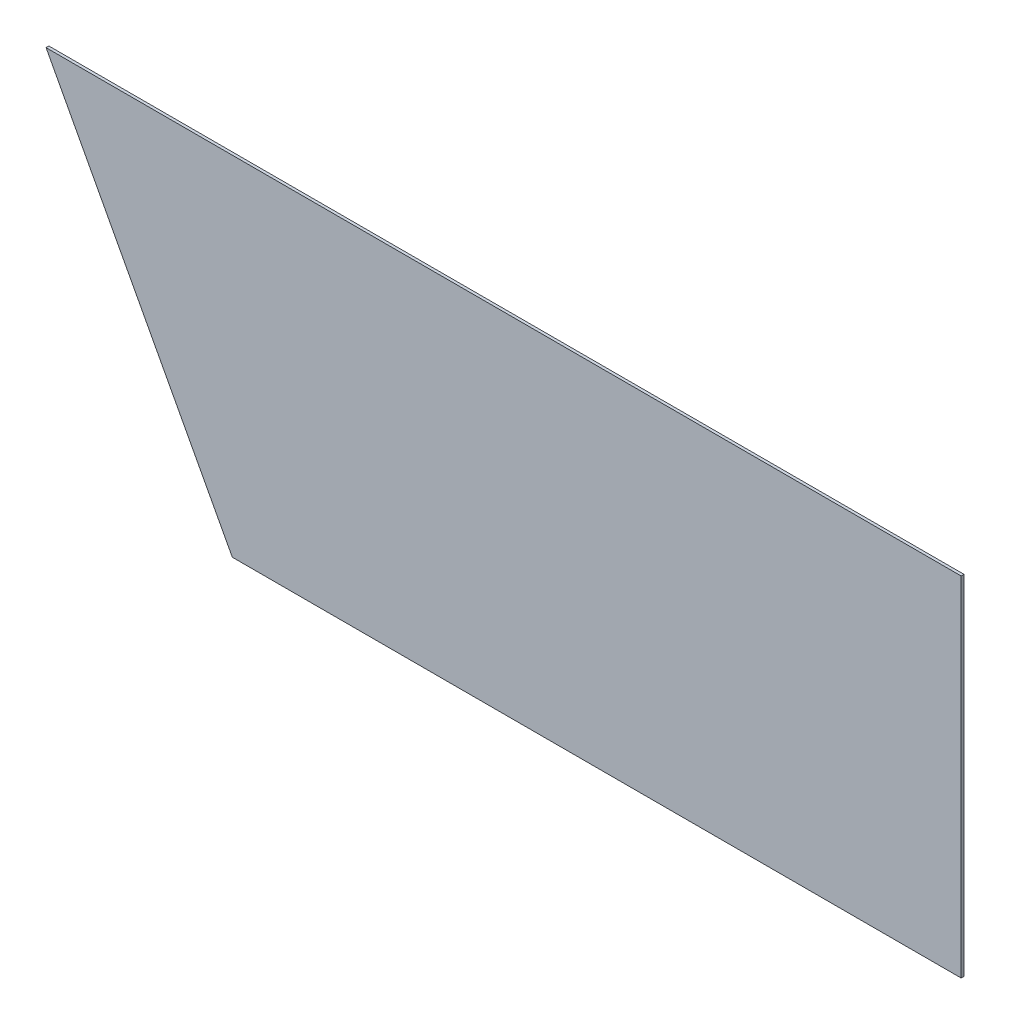
SolidWorks part; units mm, degrees
ref_plane "Plano frontal" through (0, 0, 0) normal (0, 0, 1) x (1, 0, 0)
ref_plane "Plano superior" through (0, 0, 0) normal (0, 1, 0) x (1, 0, 0)
ref_plane "Plano direito" through (0, 0, 0) normal (1, 0, 0) x (0, 0, -1)
sketch "Esboço1" plane through (0, 0, 0) normal (0, 0, 1) x (1, 0, 0)
  line L0 (-5.65, 2.15) -> (-3.35, -2.15)
  line L1 (-3.35, -2.15) -> (5.65, -2.15)
  line L3 (-5.65, 2.15) -> (5.65, 2.15)
  line L4 (5.65, -2.15) -> (5.65, 2.15)
  line L5 (-3.739, -1.4228) -> (5.65, 2.15) construction
  line L6 (-5.65, 2.15) -> (5.65, -2.15) construction
  point P0 (0, 0)
  dimension "D1" = 11.3
  dimension "D2" = 4.3
  dimension "D3" = 9
extrude "Ressalto-extrusão1" add sketch "Esboço1" along normal blind 0.035
